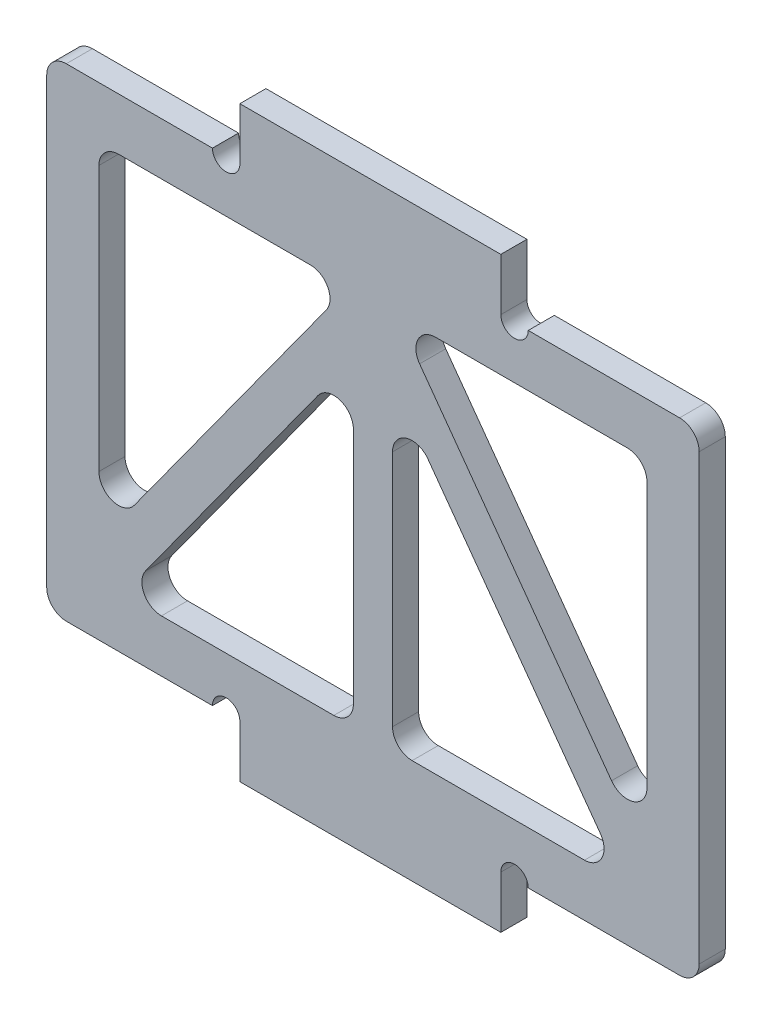
SolidWorks part; units mm, degrees
material "Thornel Mat VMA"
ref_plane "前视基准面" through (0, 0, 0) normal (0, 0, 1) x (1, 0, 0)
ref_plane "上视基准面" through (0, 0, 0) normal (0, 1, 0) x (1, 0, 0)
ref_plane "右视基准面" through (0, 0, 0) normal (1, 0, 0) x (0, 0, -1)
sketch "草图1" plane through (0, 0, 0) normal (0, 0, 1) x (1, 0, 0)
  line L1 (-25, -18.5) -> (25, -18.5)
  line L2 (-25, -18.5) -> (-25, 18.5)
  line L3 (-25, 18.5) -> (25, 18.5)
  line L4 (25, -18.5) -> (25, 18.5)
  line L5 (-25, -18.5) -> (25, 18.5) construction
  line L6 (-25, 18.5) -> (25, -18.5) construction
  point P0 (0, 0)
  dimension "D1" = 37
  dimension "D2" = 50
extrude "凸台-拉伸1" add sketch "草图1" along normal blind 2
sketch "草图2" plane through (0, 18.5, 0) normal (0, 1, 0) x (1, 0, 0)
  line L0 (9.8, -2) -> (9.8, 0) construction
  line L1 (-10.2, 0) -> (-10.2, -2) construction
  line L2 (9.8, -2) -> (9.8, 0)
  line L3 (-10.2, 0) -> (-10.2, -2)
  line L4 (-10.2, 0) -> (9.8, 0)
  line L5 (-10.2, -2) -> (9.8, -2)
extrude "凸台-拉伸2" add sketch "草图2" along normal blind 4
mirror "镜向1" about plane through (0, 0, 0) normal (0, 1, 0) of "凸台-拉伸2"
sketch "草图3" plane through (0, 0, 0) normal (0, 0, -1) x (-1, 0, 0)
  line L0 (10.2, 18.5) -> (25, 18.5) construction
  line L1 (-25, 18.5) -> (-9.8, 18.5) construction
  line L2 (-9.8, -18.5) -> (-25, -18.5) construction
  line L3 (25, -18.5) -> (10.2, -18.5) construction
  circle A0 centre (11.25, 18.5) radius 1.05
  circle A1 centre (-10.85, 18.5) radius 1.05
  circle A2 centre (-10.85, -18.5) radius 1.05
  circle A3 centre (11.25, -18.5) radius 1.05
  dimension "D1" = 2.1
extrude "切除-拉伸1" cut sketch "草图3" against normal blind 3
sketch "草图4" plane through (0, 0, 0) normal (0, 0, -1) x (-1, 0, 0)
  line L0 (12.3, 18.5) -> (25, 18.5) construction
  line L1 (-21, -14.5) -> (21, -14.5)
  line L2 (-21, -14.5) -> (-21, 14.5)
  line L3 (-21, 14.5) -> (21, 14.5)
  line L4 (21, -14.5) -> (21, 14.5)
  line L5 (0, 14.5) -> (0, -14.5) construction
  line L6 (-21, 0) -> (21, 0) construction
  line L7 (25, 18.5) -> (25, -18.5) construction
  line L8 (0, 14.5) -> (-21, -14.5) construction
  line L9 (0, 14.5) -> (21, -14.5) construction
  line L10 (-1.2149, 13.6202) -> (19.7851, -15.3798)
  line L11 (-1.2149, 15.3798) -> (-22.2149, -13.6202)
  line L12 (-1.5, 14.5) -> (-1.5, -14.5)
  line L13 (1.2149, 15.3798) -> (22.2149, -13.6202)
  line L14 (1.2149, 13.6202) -> (-19.7851, -15.3798)
  line L15 (1.5, 14.5) -> (1.5, -14.5)
  arc A0 (-1.2149, 13.6202) -> (1.2149, 15.3798) centre (0, 14.5) cw
  arc A1 (19.7851, -15.3798) -> (22.2149, -13.6202) centre (21, -14.5) ccw
  arc A2 (-1.2149, 15.3798) -> (1.2149, 13.6202) centre (0, 14.5) cw
  arc A3 (-22.2149, -13.6202) -> (-19.7851, -15.3798) centre (-21, -14.5) ccw
  arc A4 (-1.5, 14.5) -> (1.5, 14.5) centre (0, 14.5) cw
  arc A5 (-1.5, -14.5) -> (1.5, -14.5) centre (0, -14.5) ccw
  point P0 (0, 0)
  dimension "D1" = 4
  dimension "D2" = 4
  dimension "D3" = 1.5
  dimension "D4" = 1.5
extrude "切除-拉伸3" cut sketch "草图4" against normal blind 10 contours L11 L3 L2 | L12 L14 L1 | L10 L15 L1 | L3 L13 L4
fillet "圆角1" radius 1.5 16 edges at (-25, 18.5, 1) (-25, -18.5, 1) (25, -18.5, 1) (25, 18.5, 1) (1.5, -14.5, 1) (19.148, -14.5, 1) (1.5, 9.8711, 1) (-21, -11.9425, 1) (-1.852, 14.5, 1) (21, -11.9425, 1) (21, 14.5, 1) (1.852, 14.5, 1) (-1.5, -14.5, 1) (-1.5, 9.8711, 1) (-19.148, -14.5, 1) (-21, 14.5, 1)
